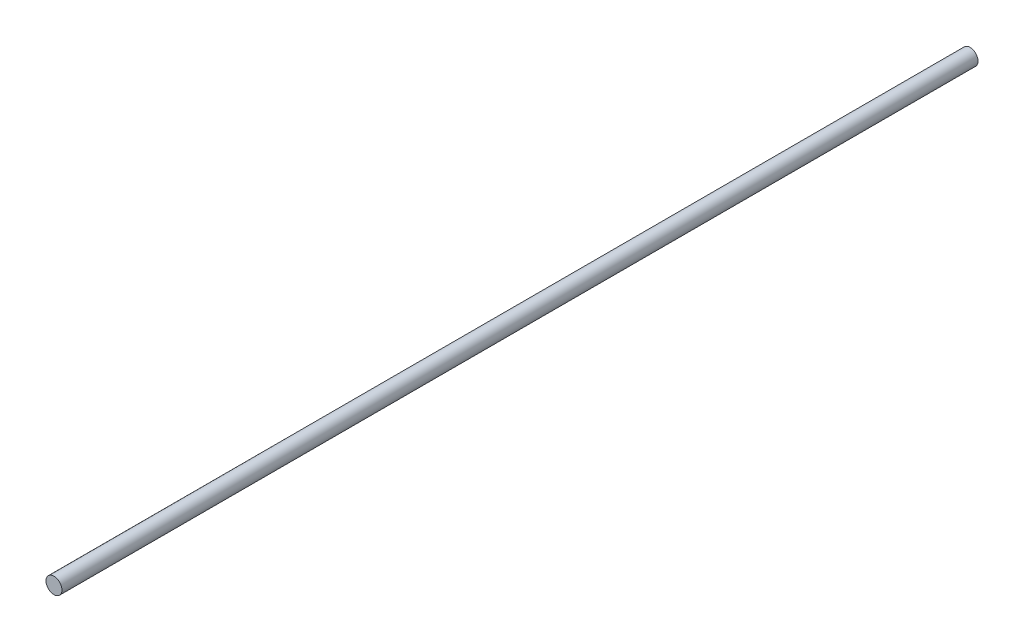
SolidWorks part; units mm, degrees
material "AISI 347 Annealed Stainless Steel (SS)"
ref_plane "Front Plane" through (0, 0, 0) normal (0, 0, 1) x (1, 0, 0)
ref_plane "Top Plane" through (0, 0, 0) normal (0, 1, 0) x (1, 0, 0)
ref_plane "Right Plane" through (0, 0, 0) normal (1, 0, 0) x (0, 0, -1)
sketch "Sketch1" plane through (0, 0, 0) normal (0, 0, 1) x (1, 0, 0)
  circle A0 centre (0, 0) radius 5
  dimension "D1" = 10
extrude "Boss-Extrude1" add sketch "Sketch1" along normal blind 574
